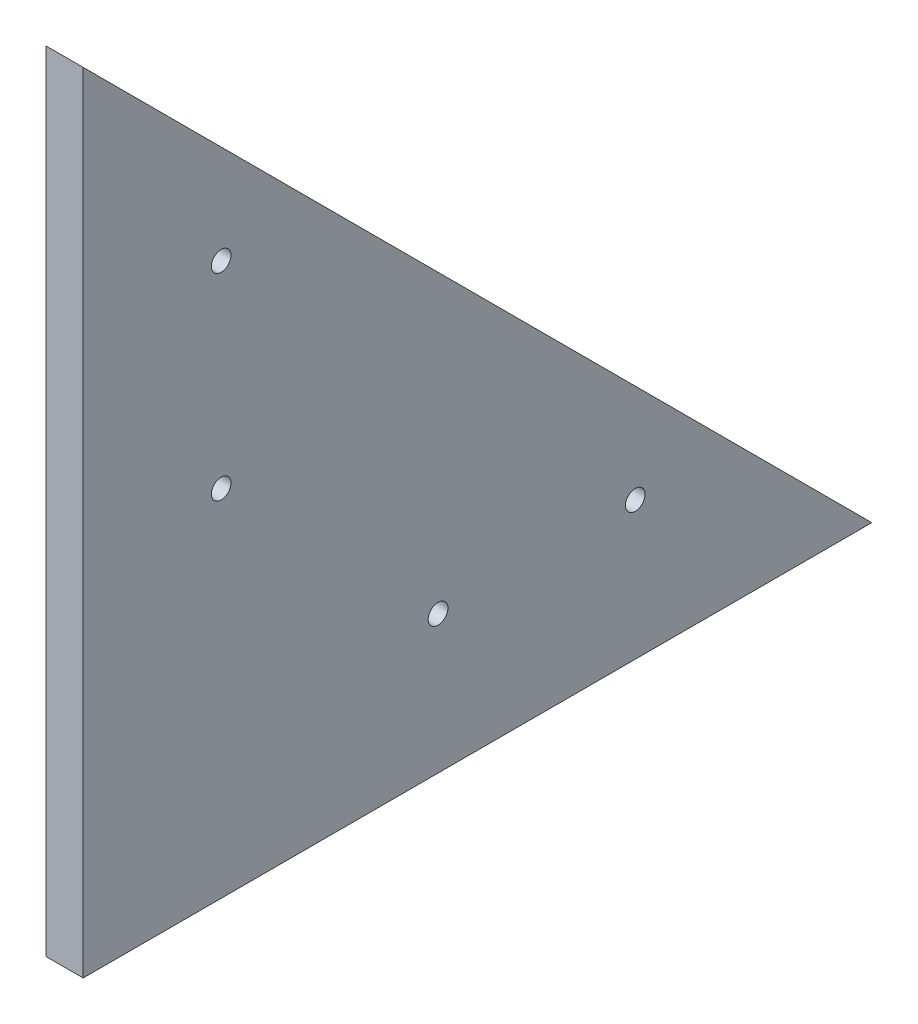
SolidWorks part; units mm, degrees
ref_plane "Front" through (0, 0, 0) normal (0, 0, 1) x (1, 0, 0)
ref_plane "Top" through (0, 0, 0) normal (0, 1, 0) x (1, 0, 0)
ref_plane "Right" through (0, 0, 0) normal (1, 0, 0) x (0, 0, -1)
sketch "Sketch1" plane through (0, 0, 0) normal (1, 0, 0) x (0, 0, -1)
  line L0 (0, 0) -> (0, 254)
  line L1 (0, 254) -> (254, 0)
  line L2 (254, 0) -> (0, 0)
  dimension "D1" = 254
  dimension "D2" = 45
extrude "Boss-Extrude1" add sketch "Sketch1" along normal blind 11.9062
hole_wizard "1/4 (0.25) Diameter Hole1" positions "Sketch2" profile "Sketch3" hole size "1/4" standard "ANSI Inch" end condition through all
sketch "Sketch2" plane through (0, 0, 0) normal (-1, 0, 0) x (0, 0, 1)
  line L0 (0, 254) -> (0, 0) construction
  line L1 (0, 0) -> (-254, 0) construction
  point P0 (-114.3, 44.45)
  point P7 (-44.45, 114.3)
  point P11 (-44.45, 177.8)
  point P14 (-177.8, 44.45)
  dimension "D1" = 44.45
  dimension "D2" = 44.45
  dimension "D3" = 44.45
  dimension "D4" = 44.45
  dimension "D5" = 63.5
  dimension "D6" = 114.3
  dimension "D7" = 114.3
  dimension "D8" = 63.5
sketch "Sketch3" plane through (0, 44.45, -114.3) normal (0, 1, 0) x (0, 0, 1)
  line L0 (0, 0) -> (0, 11.9062)
  line L1 (0, 11.9062) -> (3.175, 11.9062)
  line L2 (3.175, 11.9062) -> (3.175, 0)
  line L5 (3.175, 0) -> (0, 0)
  line L11 (0, -6.35) -> (0, 107.95) construction
  dimension "Thru Hole Dia." = 6.35
  dimension "Thru Hole Depth" = 11.9062
